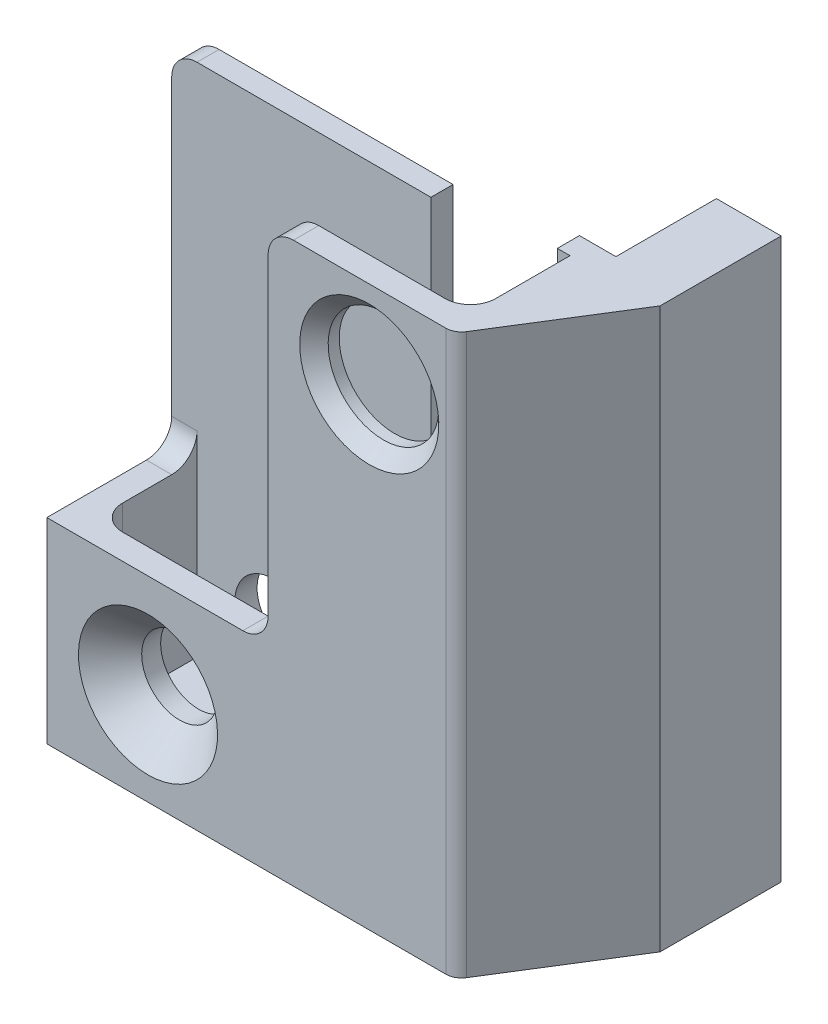
SolidWorks part; units mm, degrees
ref_plane "Front Plane" through (0, 0, 0) normal (0, 0, 1) x (1, 0, 0)
ref_plane "Top Plane" through (0, 0, 0) normal (0, 1, 0) x (1, 0, 0)
ref_plane "Right Plane" through (0, 0, 0) normal (1, 0, 0) x (0, 0, -1)
sketch "Sketch2" plane through (0, 0, 0) normal (1, 0, 0) x (0, 0, -1)
  line L0 (0, 0) -> (-4.65, 0)
  line L1 (-4.65, 0) -> (-4.65, 17.7)
  line L2 (-4.65, 17.7) -> (-3.85, 17.7)
  line L3 (-3.85, 17.7) -> (-3.85, 0.8)
  line L4 (-3.85, 0.8) -> (-0.7, 0.8)
  line L5 (-0.7, 0.8) -> (-0.7, 17.7)
  line L6 (-0.7, 17.7) -> (0, 17.7)
  line L7 (0, 17.7) -> (0, 0)
  dimension "D2" = 17.7
  dimension "D3" = 3.15
  dimension "D4" = 0.8
  dimension "D5" = 0.7
  dimension "D1" = 0.8
extrude "Boss-Extrude1" add sketch "Sketch2" along normal blind 15.4
sketch "Sketch3" plane through (0, 0, 4.65) normal (0, 0, 1) x (1, 0, 0)
  line L0 (15.4, 0) -> (0, 0) construction
  line L1 (0, 17.7) -> (7, 17.7)
  line L2 (0, 17.7) -> (0, 6.2)
  line L3 (0, 6.2) -> (7, 6.2)
  line L4 (7, 17.7) -> (7, 6.2)
  line L7 (15.4, 17.7) -> (15.4, 0) construction
  circle A0 centre (3.2, 2.95) radius 1.2 construction
  circle A1 centre (10.2, 14.95) radius 1.2 construction
  dimension "D3" = 2.4
  dimension "D8" = 2.4
  dimension "D1" = 2.95
  dimension "D4" = 11.5
  dimension "D5" = 7
  dimension "D7" = 5.2
  dimension "D6" = 12
  dimension "D2" = 7
extrude "Cut-Extrude2" cut sketch "Sketch3" against normal up to next
sketch "Sketch4" plane through (0, 0, 4.65) normal (0, 0, 1) x (1, 0, 0)
  line L0 (0, 6.2) -> (7, 6.2) construction
  line L1 (0, 0) -> (0.8, 0)
  line L2 (0, 0) -> (0, 6.2)
  line L3 (0, 6.2) -> (0.8, 6.2)
  line L4 (0.8, 0) -> (0.8, 6.2)
  line L5 (15.4, 17.7) -> (7, 17.7) construction
  line L6 (15.4, 0) -> (12.6, 0)
  line L7 (15.4, 0) -> (15.4, 17.7)
  line L8 (15.4, 17.7) -> (12.6, 17.7)
  line L9 (12.6, 0) -> (12.6, 17.7)
  dimension "D1" = 0.8
  dimension "D2" = 2.8
extrude "Boss-Extrude3" add sketch "Sketch4" against normal through all
sketch "Sketch10" plane through (0, 17.7, 0) normal (0, 1, 0) x (1, 0, 0)
  line L1 (12.6, -0.7) -> (0.8, -0.7) construction
  line L3 (12.2, -0.7) -> (12.2, 0)
  line L4 (15.4, 0) -> (0, 0) construction
  line L5 (12.2, 0) -> (8.2, 0)
  line L6 (8.2, 0) -> (8.2, -0.7)
  line L9 (12.6, -0.7) -> (0, -0.7) construction
  line L10 (8.2, -0.7) -> (12.2, -0.7)
  line L11 (15.4, 0) -> (0, 0) construction
  point P0 (12.6, 0)
  point P1 (10.2, 0)
  dimension "D1" = 4
  dimension "D2" = 2.4
extrude "Cut-Extrude4" cut sketch "Sketch10" against normal blind 16.3
sketch "Sketch6" plane through (0, 0, 3.85) normal (0, 0, -1) x (-1, 0, 0)
  line L0 (-15.4, 0) -> (-15.4, 17.7) construction
  line L1 (-14.6, 17.6) -> (-8.35, 17.6) construction
  line L2 (-14.6, 17.6) -> (-14.6, 13.1) construction
  line L3 (-14.6, 13.1) -> (-10.2, 13.1) construction
  line L4 (-8.35, 17.6) -> (-8.35, 14.95) construction
  line L5 (-0.8, 0.8) -> (-5.05, 0.8)
  line L6 (-0.8, 0.8) -> (-0.8, 4.8)
  line L7 (-0.8, 4.8) -> (-3.2, 4.8)
  line L8 (-5.05, 0.8) -> (-5.05, 2.95)
  arc A0 (-10.2, 13.1) -> (-8.35, 14.95) centre (-10.2, 14.95) ccw construction
  arc A1 (-3.2, 4.8) -> (-5.05, 2.95) centre (-3.2, 2.95) ccw
  dimension "D2" = 1.85
  dimension "D1" = 1.85
  dimension "D3" = 0.8
extrude "Boss-Extrude4" add sketch "Sketch6" along normal blind 0.8
hole_wizard "CSK for M2 Flat Head Machine Screw3" positions "3DSketch3" profile "Sketch8" countersink size "M2" standard "ANSI Metric" end condition through all
sketch3d "3DSketch3"
  point P0 (10.2, 14.95, 4.65)
  point P3 (3.2, 2.95, 4.65)
sketch "Sketch8" plane through (10.2, 14.95, 4.65) normal (1, 0, 0) x (0, -1, 0)
  line L0 (0, 0) -> (0, 4.65)
  line L1 (0, 4.65) -> (1.2, 4.65)
  line L2 (1.2, 4.65) -> (1.2, 1)
  line L3 (1.2, 1) -> (2.2, 0)
  line L5 (2.2, 0) -> (0, 0)
  line L6 (-1.2, 1) -> (-2.2, 0) construction
  line L11 (0, -6.35) -> (0, 107.95) construction
  dimension "Thru Hole Dia." = 2.4
  dimension "Thru Hole Depth" = 4.65
  dimension "Near C'Sink Dia." = 4.4
  dimension "Near C'Sink Angle" = 90
other "Move Face1" face at (4.1, 17.7, 0.35) parameters "D1"=0.6
fillet "Fillet3" radius 0.8 6 edges at (0.8, 5.5, 3.85) (12.6, 9.25, 3.85) (0.4, 6.2, 0.7) (7, 6.2, 4.25) (7, 17.7, 4.25) (0, 17.1, 0.35)
chamfer "Chamfer1" distance 2.5 distance2 4 1 edges at (15.4, 8.85, 4.65)
sketch "Sketch12" plane through (0, 17.7, 0) normal (0, 1, 0) x (1, 0, 0)
  line L0 (16.5389, 2.7148) -> (17.5509, -0.4) construction
  line L1 (13.3525, 0) -> (15.4, 0)
  line L2 (13.3525, 0) -> (13.3525, 3.18)
  line L3 (13.3525, 3.18) -> (15.4, 3.18)
  line L4 (15.4, 0) -> (15.4, 3.18)
  line L5 (17.5509, -0.4) -> (16.9803, -0.5854) construction
  line L7 (15.9205, 2.2148) -> (16.0705, 2.2148) construction
  line L8 (16.0705, 2.2148) -> (16.9803, -0.5854) construction
  dimension "D1" = 3.18
  dimension "D2" = 0.15
  dimension "D3" = 0.6
  dimension "D4" = 0.5
  dimension "D5" = 18
  dimension "D6" = 0.4
  dimension "D7" = 0.7525
extrude "Boss-Extrude5" add sketch "Sketch12" against normal blind 17.7
fillet "Fillet5" radius 0.5 1 edges at (12.9, 8.85, 4.65)
sketch "Sketch11" plane through (0, 0, 3.85) normal (0, 0, -1) x (-1, 0, 0)
  circle A0 centre (-10.2, 14.95) radius 1.75
  dimension "D1" = 3.5
extrude "Cut-Extrude5" cut sketch "Sketch11" against normal through all and the other way up to next
delete or keep bodies "Body-Delete/Keep 1" [suppressed] type delete bodies bodies 112
mirror "Mirror1" [suppressed]
delete or keep bodies "Body-Delete/Keep 2" [suppressed] type delete bodies bodies 114
equation "\"BoardLength\"= 11'mech 305"
equation "\"BoardHeight\"= 16'is"
equation "\"BoardThickness\"= 3'pain"
equation "\"ScrewHoleDiameter\"= 2.4'and"
equation "\"PrintThickness\"= 0.8'suffering"
equation "\"D2@Sketch2\"=\"BoardHeight\"+\"PrintThickness\"+\"Tolerance\"+0.75"
equation "\"D3@Sketch2\"=\"BoardThickness\"+\"Tolerance\""
equation "\"D4@Sketch2\"=\"PrintThickness\""
equation "\"D1@Boss-Extrude1\"=\"BoardLength\"+\"PrintThickness\"*2+\"Tolerance\"*2+1.5+1"
equation "\"D3@Sketch3\"=\"ScrewHoleDiameter\""
equation "\"D1@Sketch3\"=\"PrintThickness\"+2+\"Tolerance\""
equation "\"D1@Sketch4\"=\"PrintThickness\""
equation "\"D7@Sketch3\"=\"PrintThickness\"+3.25+\"Tolerance\"+1"
equation "\"D8@Sketch3\"=\"ScrewHoleDiameter\""
equation "\"MetalRingOuterDiameter\"= 3.7'drop it"
equation "\"D2@Sketch6\"=\"MetalRingOuterDiameter\"/2"
equation "\"DribblerPlateThickness\"= 3.18"
equation "\"D1@Sketch6\"=\"MetalRingOuterDiameter\"/2"
equation "\"Tolerance\"= 0.15"
equation "\"D2@Sketch4\"=\"PrintThickness\"+1+1"
equation "\"D1@Sketch2\"=\"PrintThickness\""
equation "\"D1@Cut-Extrude4\"=\"BoardHeight\"+\"Tolerance\"*2"
